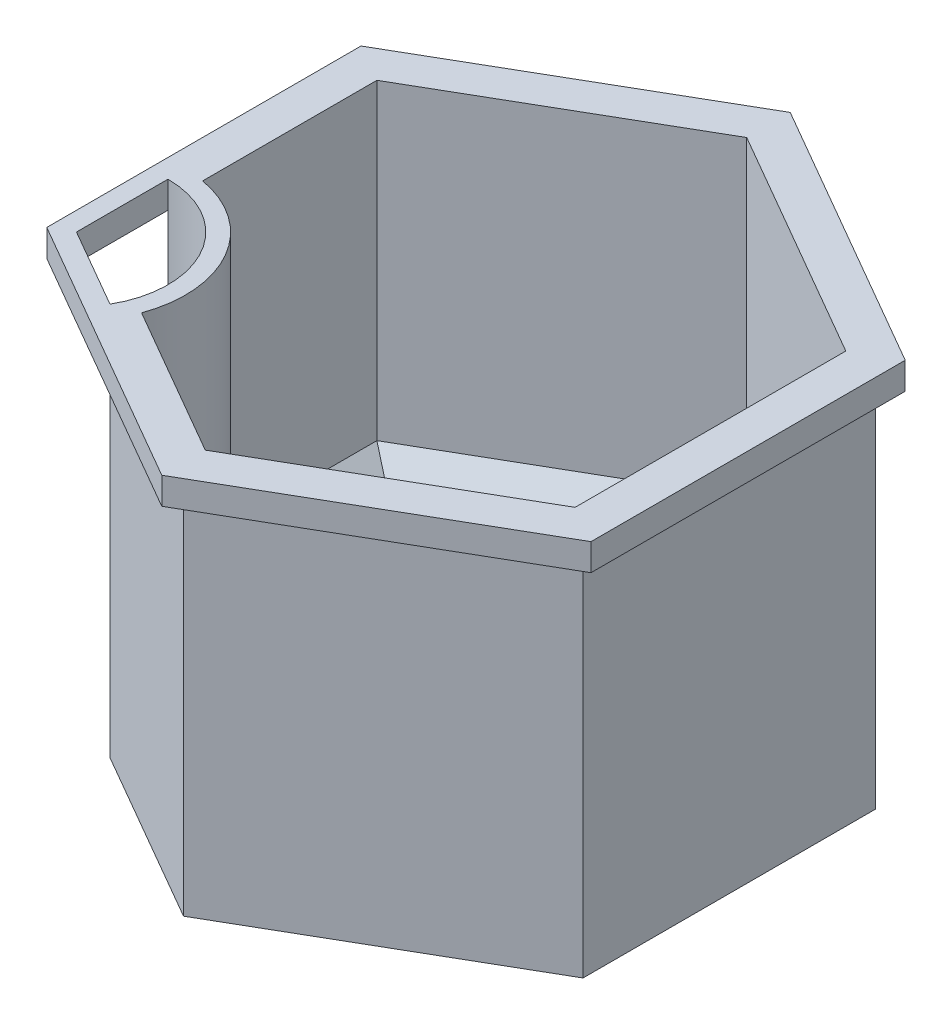
SolidWorks part; units mm, degrees
ref_plane "Front Plane" through (0, 0, 0) normal (0, 0, 1) x (1, 0, 0)
ref_plane "Top Plane" through (0, 0, 0) normal (0, 1, 0) x (1, 0, 0)
ref_plane "Right Plane" through (0, 0, 0) normal (1, 0, 0) x (0, 0, -1)
sketch "Sketch3" plane through (0, 0, 0) normal (0, 1, 0) x (1, 0, 0)
  line L1 (50.5773, -29.2008) -> (50.5773, 29.2008)
  line L2 (50.5773, 29.2008) -> (0, 58.4016)
  line L3 (0, 58.4016) -> (-50.5773, 29.2008)
  line L4 (-50.5773, 29.2008) -> (-50.5773, -29.2008)
  line L5 (-50.5773, -29.2008) -> (0, -58.4016)
  line L6 (0, -58.4016) -> (50.5773, -29.2008)
  line L7 (43.5773, -25.1593) -> (43.5773, 25.1593)
  line L8 (43.5773, 25.1593) -> (0, 50.3187)
  line L9 (0, 50.3187) -> (-43.5773, 25.1593)
  line L10 (-43.5773, 25.1593) -> (-43.5773, -25.1593)
  line L11 (-43.5773, -25.1593) -> (0, -50.3187)
  line L12 (0, -50.3187) -> (43.5773, -25.1593)
  circle A0 centre (0, 0) radius 43.5773 construction
  dimension "D1" = 116.8032
  dimension "D2" = 7
extrude "Boss-Extrude1" add sketch "Sketch3" along normal blind 5
sketch "Sketch4" plane through (0, 5, 0) normal (0, 1, 0) x (1, 0, 0)
  line L0 (-50.5773, 29.2008) -> (-50.5773, -29.2008) construction
  line L1 (47.0773, -27.1801) -> (47.0773, 27.1801)
  line L2 (47.0773, 27.1801) -> (0, 54.3601)
  line L3 (0, 54.3601) -> (-47.0773, 27.1801)
  line L4 (-47.0773, 27.1801) -> (-47.0773, -27.1801)
  line L5 (-47.0773, -27.1801) -> (0, -54.3601)
  line L6 (0, -54.3601) -> (47.0773, -27.1801)
  circle A0 centre (0, 0) radius 47.0773 construction
  dimension "D1" = 3.5
extrude "Boss-Extrude2" add sketch "Sketch4" against normal blind 73
sketch "Sketch5" plane through (0, 5, 0) normal (0, 1, 0) x (1, 0, 0)
  line L0 (-50.5773, 29.2008) -> (-50.5773, -29.2008) construction
  line L1 (43.5773, -25.1593) -> (43.5773, 25.1593)
  line L2 (43.5773, 25.1593) -> (0, 50.3187)
  line L3 (0, 50.3187) -> (-43.5773, 25.1593)
  line L4 (-43.5773, 25.1593) -> (-43.5773, -25.1593)
  line L5 (-43.5773, -25.1593) -> (0, -50.3187)
  line L6 (0, -50.3187) -> (43.5773, -25.1593)
  circle A0 centre (0, 0) radius 43.5773 construction
  dimension "D1" = 7
extrude "Cut-Extrude1" cut sketch "Sketch5" against normal blind 68
sketch "Sketch6" plane through (0, 5, 0) normal (0, 1, 0) x (1, 0, 0)
  line L0 (-47.0773, -10.8875) -> (-47.0773, -27.2103)
  line L1 (-47.0773, -27.2103) -> (-32.9283, -35.349)
  line L2 (-50.5773, 29.2008) -> (-50.5773, -29.2008) construction
  line L3 (-50.5773, -29.2008) -> (0, -58.4016) construction
  line L4 (-47.0773, -6.9294) -> (-47.0773, -27.2103)
  line L5 (-29.5939, -37.4887) -> (-47.0773, -27.2103)
  arc A1 (-47.0773, -6.9294) -> (-29.5939, -37.4887) centre (-47.0773, -27.2103) cw
  line M3 (0, -50.3187) -> (-43.5773, -25.1593)
  line M4 (-43.5773, -25.1593) -> (-43.5773, 25.1593)
  dimension "D1" = 3.5
  dimension "D2" = 3.5
extrude "Boss-Extrude3" add sketch "Sketch6" against normal blind 73 contours A1 M4 M3
sketch "Sketch9" plane through (0, 5, 0) normal (0, 1, 0) x (1, 0, 0)
  line L0 (-47.0773, -10.1801) -> (-47.0773, -27.1801)
  line L2 (-50.5773, 29.2008) -> (-50.5773, -29.2008) construction
  line L3 (-47.0773, -27.1801) -> (-32.3548, -35.6801)
  line L4 (-50.5773, -29.2008) -> (0, -58.4016) construction
  arc A1 (-47.0773, -10.1801) -> (-32.3548, -35.6801) centre (-47.0773, -27.1801) cw
  dimension "D2" = 17
  dimension "D1" = 3.5
  dimension "D3" = 17
  dimension "D4" = 3.5
extrude "Cut-Extrude3" cut sketch "Sketch9" against normal blind 73
chamfer "Chamfer1" distance 10 angle 45 6 edges at (-43.5773, -63, -8.9628) (-21.7886, -63, -37.739) (21.7886, -63, -37.739) (43.5773, -63, 0) (21.7886, -63, 37.739) (-14.009, -63, 42.2306)
